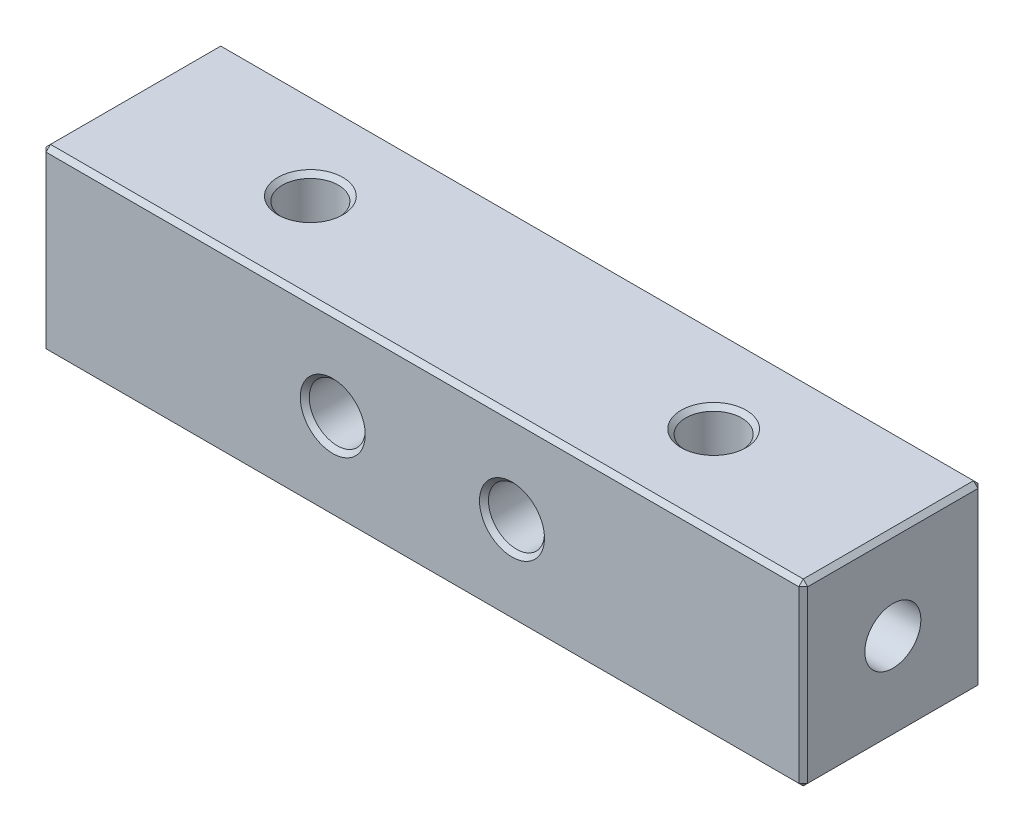
SolidWorks part; units mm, degrees
ref_plane "前视基准面" through (0, 0, 0) normal (0, 0, 1) x (1, 0, 0)
ref_plane "上视基准面" through (0, 0, 0) normal (0, 1, 0) x (1, 0, 0)
ref_plane "右视基准面" through (0, 0, 0) normal (1, 0, 0) x (0, 0, -1)
sketch "草图1" plane through (0, 0, 0) normal (0, 1, 0) x (1, 0, 0)
  line L1 (-17, 4) -> (17, 4)
  line L2 (-17, 4) -> (-17, -4)
  line L3 (-17, -4) -> (17, -4)
  line L4 (17, 4) -> (17, -4)
  line L5 (-17, 4) -> (17, -4) construction
  line L6 (-17, -4) -> (17, 4) construction
  point P0 (0, 0)
  dimension "D1" = 8
  dimension "D2" = 34
extrude "凸台-拉伸1" add sketch "草图1" along normal mid plane 8
hole_wizard "M3 螺纹孔1" positions "草图4" profile "草图6" tap size "M3" standard "GB" end condition through all
sketch "草图4" plane through (0, 4, 0) normal (0, 1, 0) x (1, 0, 0)
  line L0 (-17, 4) -> (-17, -4) construction
  line L1 (0, 0) -> (-50000, 0) construction
  point P0 (-9, 0)
  point P2 (9, 0)
  dimension "D1" = 8
  dimension "D2" = 18
sketch "草图6" plane through (-9, 4, 0) normal (1, 0, 0) x (0, 0, 1)
  line L0 (0, 0) -> (0, 8)
  line L1 (0, 8) -> (1.25, 8)
  line L2 (1.25, 8) -> (1.25, 0)
  line L5 (1.25, 0) -> (0, 0)
  line L11 (0, -6.35) -> (0, 107.95) construction
  dimension "通孔螺纹孔钻头直径" = 2.5
  dimension "通孔螺纹孔钻头深度" = 8
cosmetic thread "孔螺蚊线1"
cosmetic thread "孔螺蚊线2"
hole_wizard "M3 螺纹孔2" positions "草图7" profile "草图8" tap size "M3" standard "GB" end condition through all
sketch "草图7" plane through (0, 0, -4) normal (0, 0, -1) x (-1, 0, 0)
  line L0 (0, 0) -> (-50000, 0) construction
  line L1 (-17, 4) -> (-17, -4) construction
  point P0 (-4, 0)
  point P2 (4, 0)
  dimension "D1" = 13
  dimension "D2" = 8
sketch "草图8" plane through (4, 0, -4) normal (1, 0, 0) x (0, 1, 0)
  line L0 (0, 0) -> (0, 8)
  line L1 (0, 8) -> (1.25, 8)
  line L2 (1.25, 8) -> (1.25, 0)
  line L5 (1.25, 0) -> (0, 0)
  line L11 (0, -6.35) -> (0, 107.95) construction
  dimension "通孔螺纹孔钻头直径" = 2.5
  dimension "通孔螺纹孔钻头深度" = 8
cosmetic thread "孔螺蚊线3"
cosmetic thread "孔螺蚊线4"
chamfer "倒角1" distance 0.2 angle 45 20 edges at (9, -4, 1.25) (-9, -4, 1.25) (-5.25, 0, 4) (2.75, 0, 4) (9, 4, 1.25) (-9, 4, 1.25) (-17, -4, 0) (17, -4, 0) (-17, 0, 4) (0, -4, 4) (17, 0, 4) (0, 4, 4) (-17, 4, 0) (17, 4, 0) (17, 0, -4) (0, 4, -4) (-17, 0, -4) (0, -4, -4) (-5.25, 0, -4) (2.75, 0, -4)
hole_wizard "M3 螺纹孔3" positions "草图9" profile "草图10" tap size "M3" standard "GB"
sketch "草图9" plane through (-17, 0, 0) normal (-1, 0, 0) x (0, 0, 1)
  point P0 (0, 0)
sketch "草图10" plane through (-17, 0, 0) normal (0, 1, 0) x (0, 0, 1)
  line L0 (0, 0) -> (0, 6.75)
  line L1 (0, 6.75) -> (1.25, 6.75)
  line L2 (1.25, 6.75) -> (1.25, 0)
  line L5 (1.25, 0) -> (0, 0)
  line L11 (0, -6.35) -> (0, 107.95) construction
  dimension "通孔螺纹孔钻头直径" = 2.5
  dimension "通孔螺纹孔钻头深度" = 6.75
cosmetic thread "孔螺蚊线5"
hole_wizard "M3 螺纹孔4" positions "草图11" profile "草图12" tap size "M3" standard "GB"
sketch "草图11" plane through (17, 0, 0) normal (1, 0, 0) x (0, 0, -1)
  point P0 (0, 0)
sketch "草图12" plane through (17, 0, 0) normal (0, 1, 0) x (0, 0, -1)
  line L0 (0, 0) -> (0, 6.75)
  line L1 (0, 6.75) -> (1.25, 6.75)
  line L2 (1.25, 6.75) -> (1.25, 0)
  line L5 (1.25, 0) -> (0, 0)
  line L11 (0, -6.35) -> (0, 107.95) construction
  dimension "通孔螺纹孔钻头直径" = 2.5
  dimension "通孔螺纹孔钻头深度" = 6.75
cosmetic thread "孔螺蚊线6" parameters "D2"=3
